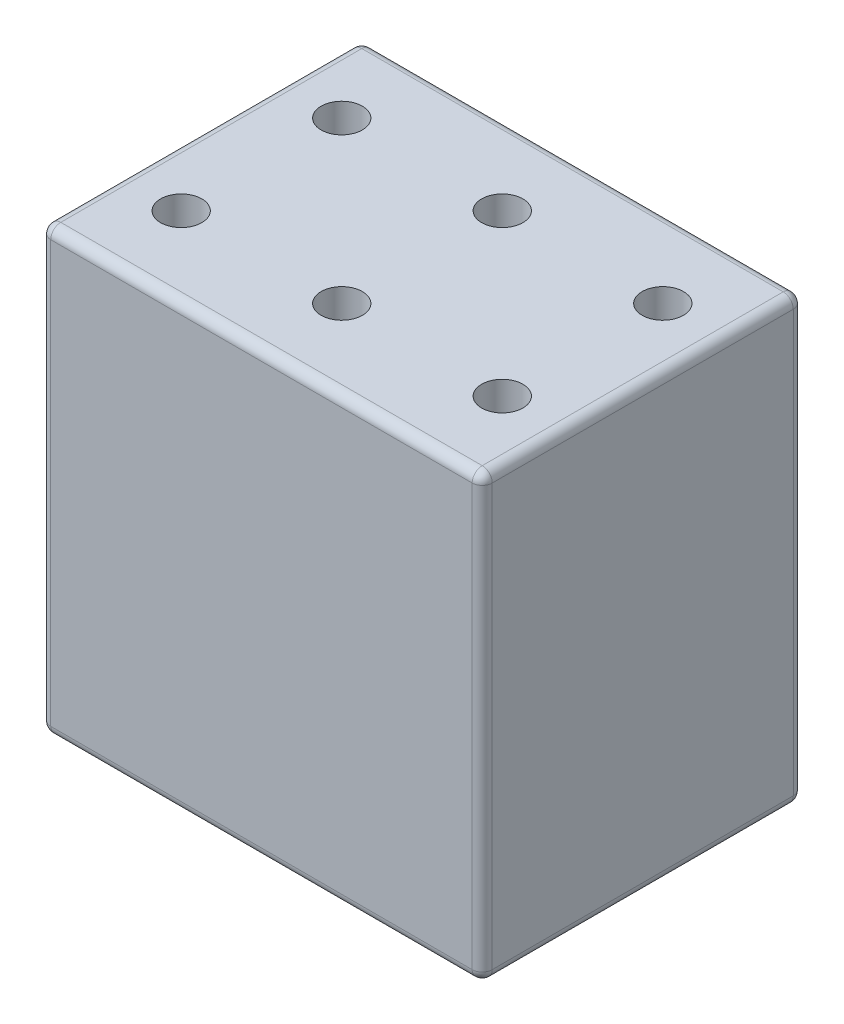
SolidWorks part; units mm, degrees
ref_plane "Front Plane" through (0, 0, 0) normal (0, 0, 1) x (1, 0, 0)
ref_plane "Top Plane" through (0, 0, 0) normal (0, 1, 0) x (1, 0, 0)
ref_plane "Right Plane" through (0, 0, 0) normal (1, 0, 0) x (0, 0, -1)
sketch "Sketch1" plane through (0, 0, 0) normal (0, 1, 0) x (1, 0, 0)
  line L1 (-34.925, -25.4) -> (34.925, -25.4)
  line L2 (-38.1, -25.4) -> (-38.1, 25.4) construction
  line L3 (-34.925, 25.4) -> (34.925, 25.4)
  line L4 (38.1, -25.4) -> (38.1, 25.4) construction
  line L5 (-38.1, -25.4) -> (38.1, 25.4) construction
  line L6 (-38.1, 25.4) -> (38.1, -25.4) construction
  line L7 (34.925, -25.4) -> (34.925, 25.4)
  line L8 (-34.925, -25.4) -> (-34.925, 25.4)
  circle A0 centre (-25.4, -12.7) radius 3.2639
  circle A1 centre (0, -12.7) radius 3.2639
  circle A2 centre (25.4, -12.7) radius 3.2639
  circle A3 centre (0, 12.7) radius 3.2639
  circle A4 centre (25.4, 12.7) radius 3.2639
  circle A5 centre (-25.4, 12.7) radius 3.2639
  point P0 (0, 0)
  dimension "D5" = 6.5278
  dimension "D1" = 50.8
  dimension "D2" = 76.2
  dimension "D3" = 12.7
  dimension "D4" = 12.7
  dimension "D8" = 25.4
  dimension "D9" = 35.921
  dimension "D10" = 25.4
  dimension "D11" = 3.175
  dimension "D12" = 3.175
  dimension "D6" = 3
  dimension "D7" = 2
extrude "Boss-Extrude1" add sketch "Sketch1" along normal blind 69.85
fillet "Fillet1" radius 1.5875 12 edges at (0, 69.85, -25.4) (0, 0, -25.4) (0, 69.85, 25.4) (0, 0, 25.4) (34.925, 34.925, -25.4) (-34.925, 34.925, -25.4) (-34.925, 34.925, 25.4) (34.925, 34.925, 25.4) (34.925, 69.85, 0) (34.925, 0, 0) (-34.925, 69.85, 0) (-34.925, 0, 0)
